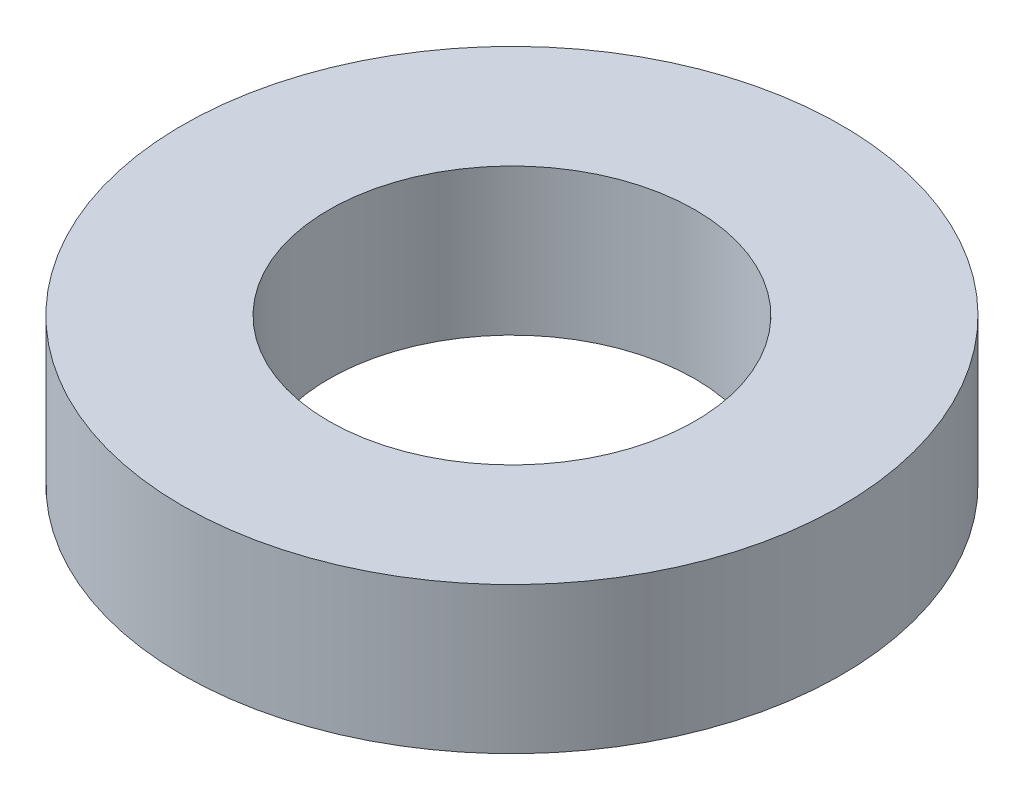
SolidWorks part; units mm, degrees
ref_plane "Front Plane" through (0, 0, 0) normal (0, 0, 1) x (1, 0, 0)
ref_plane "Top Plane" through (0, 0, 0) normal (0, 1, 0) x (1, 0, 0)
ref_plane "Right Plane" through (0, 0, 0) normal (1, 0, 0) x (0, 0, -1)
sketch "Sketch1" plane through (0, 0, 0) normal (0, 1, 0) x (1, 0, 0)
  circle A0 centre (0, 0) radius 1.5
  circle A1 centre (0, 0) radius 2.7
  dimension "D1" = 3
  dimension "D2" = 1.2
extrude "Boss-Extrude1" add sketch "Sketch1" along normal blind 1.2
